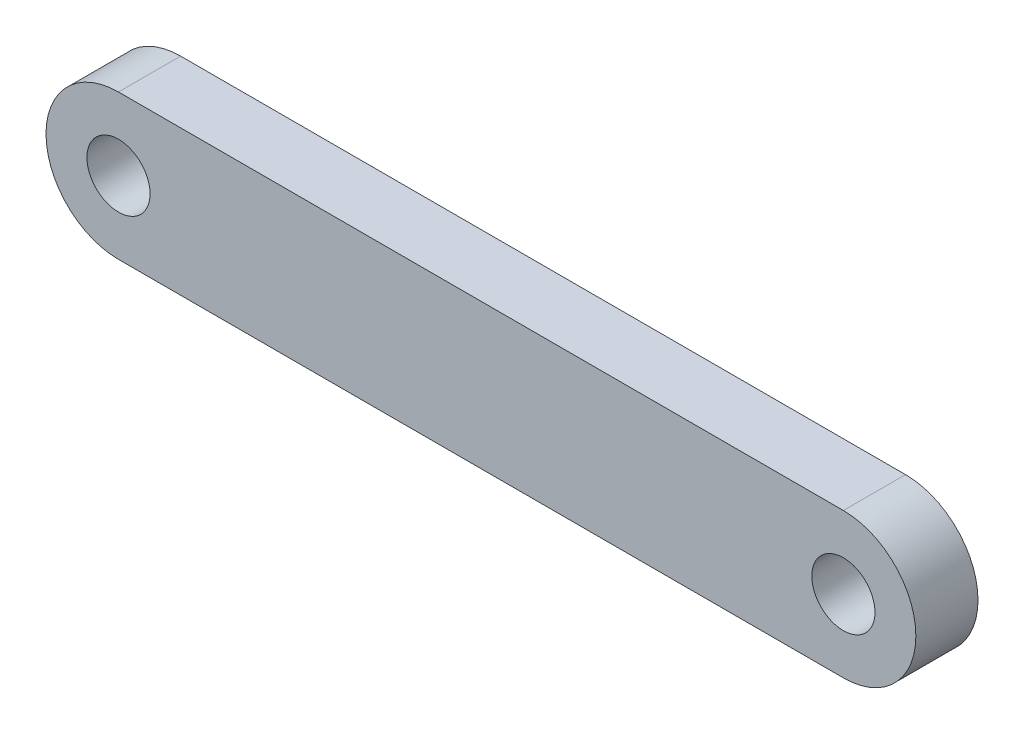
SolidWorks part; units mm, degrees
material "Balsa"
ref_plane "Front Plane" through (0, 0, 0) normal (0, 0, 1) x (1, 0, 0)
ref_plane "Top Plane" through (0, 0, 0) normal (0, 1, 0) x (1, 0, 0)
ref_plane "Right Plane" through (0, 0, 0) normal (1, 0, 0) x (0, 0, -1)
sketch "Sketch1" plane through (0, 0, 0) normal (0, 0, 1) x (1, 0, 0)
  line L0 (0, 0) -> (35, 0) construction
  line L1 (0, 3.5) -> (35, 3.5)
  line L2 (0, -3.5) -> (35, -3.5)
  line L3 (17.5, 0) -> (17.5, -3.5) construction
  arc A0 (0, 3.5) -> (0, -3.5) centre (0, 0) ccw
  arc A1 (35, -3.5) -> (35, 3.5) centre (35, 0) ccw
  arc A2 (0, 3.5) -> (0, -3.5) centre (0, 0) ccw
  circle A3 centre (0, 0) radius 1.525
  circle A4 centre (35, 0) radius 1.525
  arc A5 (35, 3.5) -> (35, -3.5) centre (35, 0) cw
  point P3 (17.5, 0)
  dimension "D3" = 3.05
  dimension "D1" = 7
  dimension "D2" = 35
extrude "Boss-Extrude1" add sketch "Sketch1" along normal mid plane 3
